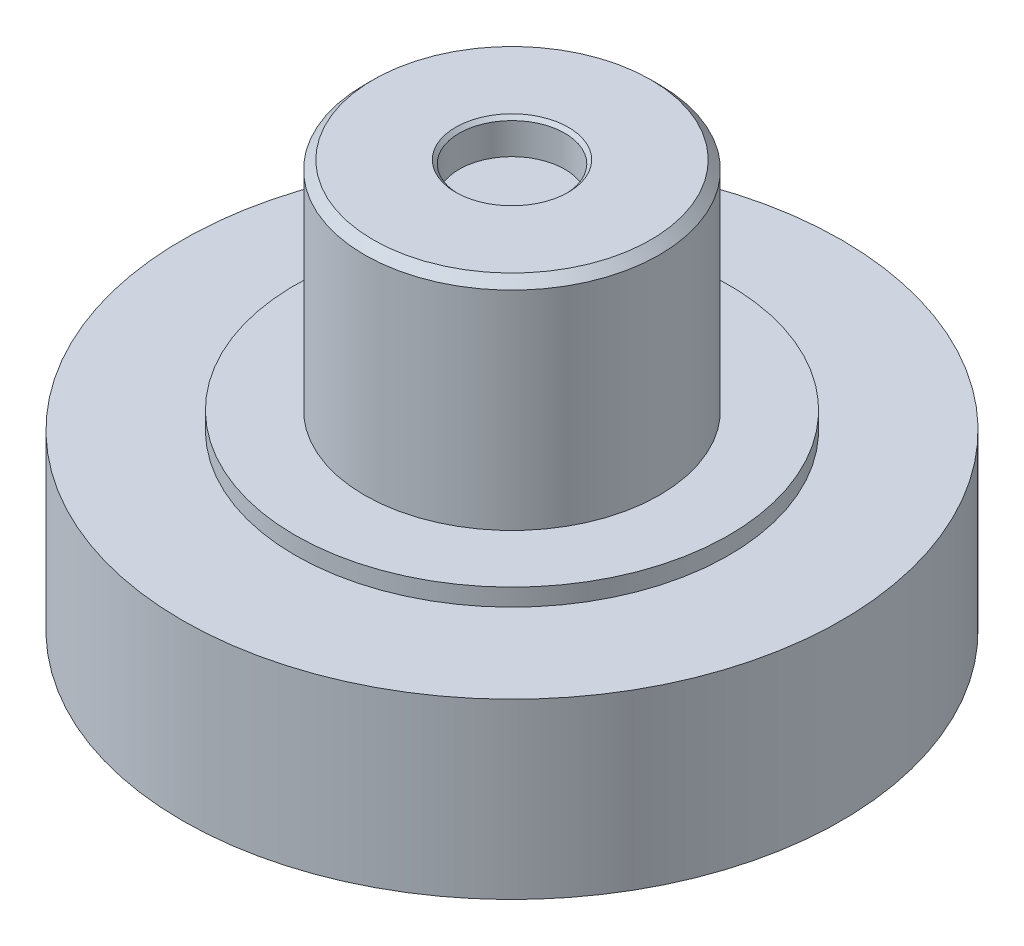
SolidWorks part; units mm, degrees
ref_plane "Спереди" through (0, 0, 0) normal (0, 0, 1) x (1, 0, 0)
ref_plane "Сверху" through (0, 0, 0) normal (0, 1, 0) x (1, 0, 0)
ref_plane "Справа" through (0, 0, 0) normal (1, 0, 0) x (0, 0, -1)
sketch "Эскиз1" plane through (0, 0, 0) normal (0, 1, 0) x (1, 0, 0)
  circle A0 centre (0, 0) radius 19
  dimension "D1" = 38
extrude "Бобышка-Вытянуть1" add sketch "Эскиз1" along normal blind 10
sketch "Эскиз2" plane through (0, 10, 0) normal (0, 1, 0) x (1, 0, 0)
  circle A0 centre (0, 0) radius 12.5
  dimension "D1" = 25
extrude "Бобышка-Вытянуть2" add sketch "Эскиз2" along normal blind 1
sketch "Эскиз3" plane through (0, 11, 0) normal (0, 1, 0) x (1, 0, 0)
  circle A0 centre (0, 0) radius 8.5
  dimension "D1" = 17
extrude "Бобышка-Вытянуть3" add sketch "Эскиз3" along normal blind 12.5
sketch "Эскиз4" plane through (0, 23.5, 0) normal (0, 1, 0) x (1, 0, 0)
  circle A0 centre (0, 0) radius 3.05
  dimension "D1" = 6.1
extrude "Вырез-Вытянуть4" cut sketch "Эскиз4" against normal blind 2
sketch "Эскиз7" plane through (0, 0, 0) normal (0, -1, 0) x (1, 0, 0)
  line L0 (0, 0) -> (-22.8361, 0) construction
  line L1 (-5.25, 0) -> (-5.25, 15.6623) construction
  circle A0 centre (0, 11.5) radius 5.25
  point P3 (-22.8361, 0)
  dimension "D1" = 10.5
  dimension "D2" = 11.5
  dimension "D3" = 5.25
extrude "Вырез-Вытянуть3" cut sketch "Эскиз7" against normal blind 0.5 draft 45
fillet "Скругление3" radius 0.8 2 edges at (0, 0, 6.25) (0, 0.5, 6.75)
chamfer "Фаска1" distance 0.5 angle 45 1 edges at (0, 23.5, 8.5)
chamfer "Фаска2" distance 0.2 angle 45 1 edges at (0, 23.5, 3.05)
equation "\"80в\"=90"
